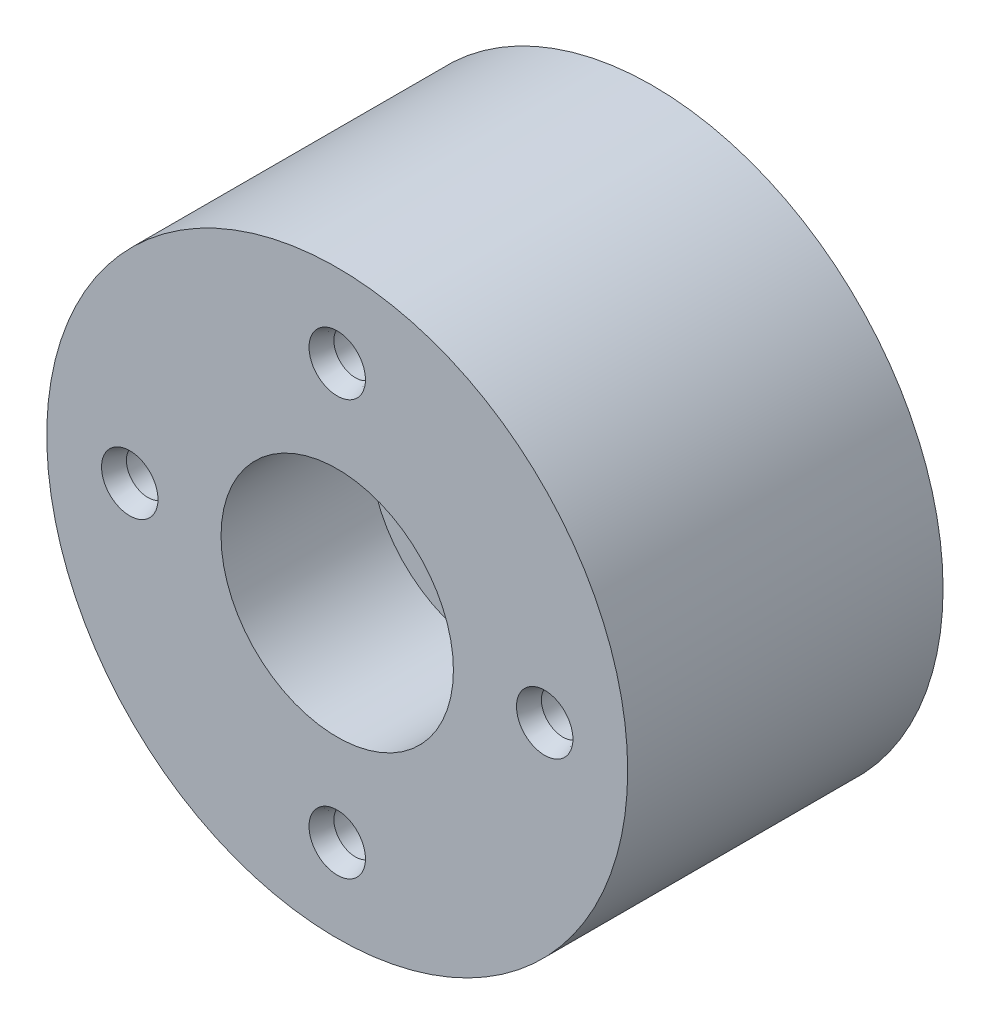
SolidWorks part; units mm, degrees
ref_plane "前视基准面" through (0, 0, 0) normal (0, 0, 1) x (1, 0, 0)
ref_plane "上视基准面" through (0, 0, 0) normal (0, 1, 0) x (1, 0, 0)
ref_plane "右视基准面" through (0, 0, 0) normal (1, 0, 0) x (0, 0, -1)
other "Configuration Table"
sketch "草图1" plane through (0, 0, 0) normal (0, 0, 1) x (1, 0, 0)
  circle A0 centre (0, 0) radius 17.5
extrude "凸台-拉伸1" add sketch "草图1" against normal blind 19
sketch "草图2" plane through (0, 0, 0) normal (0, 0, 1) x (1, 0, 0)
  circle A0 centre (12.5, 0) radius 1.3
  circle A1 centre (0, -12.5) radius 1.3
  circle A2 centre (-12.5, 0) radius 1.3
  circle A3 centre (0, 12.5) radius 1.3
  point P11 (0, 0)
  dimension "D1" = 4
extrude "切除-拉伸1" cut sketch "草图2" against normal blind 8
sketch "草图4" plane through (0, 0, 0) normal (0, 0, 1) x (1, 0, 0)
  circle A0 centre (0, 0) radius 7
extrude "切除-拉伸3" cut sketch "草图4" against normal offset from surface (9 mm away) 10 up to face at (17.5, 0, -19)
sketch "草图5" plane through (0, 0, -9) normal (0, 0, 1) x (1, 0, 0)
  circle A0 centre (0, 0) radius 5.55
extrude "切除-拉伸4" cut sketch "草图5" against normal up to surface (10 mm away) up to face at (17.5, 0, -19)
sketch "草图7" plane through (0, 0, -19) normal (0, 0, -1) x (-1, 0, 0)
  line L0 (4.6927, 14.8832) -> (13.1615, -8.3848) construction
  line L1 (0, 19.1827) -> (0, 0) construction
  line L2 (0, 0) -> (4.6927, 14.8832) construction
  line L3 (0, 0) -> (25.0264, 0) construction
  line L4 (0, 0) -> (13.1615, -8.3848) construction
  line L5 (4.6927, 14.8832) -> (5.256, 13.3355)
  line L6 (5.256, 13.3355) -> (5.8193, 11.7878)
  line L7 (5.8193, 11.7878) -> (6.3826, 10.2402)
  line L8 (6.3826, 10.2402) -> (6.9459, 8.6925)
  line L9 (6.9459, 8.6925) -> (7.5092, 7.1448)
  line L10 (7.5092, 7.1448) -> (8.0725, 5.5971)
  line L11 (8.0725, 5.5971) -> (8.6358, 4.0495)
  line L12 (8.6358, 4.0495) -> (9.1991, 2.5018)
  line L13 (9.1991, 2.5018) -> (9.7624, 0.9541)
  line L14 (9.7624, 0.9541) -> (10.3257, -0.5935)
  line L15 (10.3257, -0.5935) -> (10.889, -2.1412)
  line L16 (10.889, -2.1412) -> (11.4523, -3.6889)
  line L17 (11.4523, -3.6889) -> (12.0156, -5.2366)
  line L18 (12.0156, -5.2366) -> (12.5982, -6.8371)
  line L19 (12.5982, -6.8371) -> (13.1615, -8.3848)
  line L20 (0, 0) -> (5.256, 13.3355) construction
  line L21 (0, 0) -> (5.8193, 11.7878) construction
  line L22 (0, 0) -> (6.3826, 10.2402) construction
  line L23 (0, 0) -> (6.9459, 8.6925) construction
  line L24 (0, 0) -> (7.5092, 7.1448) construction
  line L25 (0, 0) -> (8.0725, 5.5971) construction
  line L26 (0, 0) -> (8.6358, 4.0495) construction
  line L27 (0, 0) -> (9.1991, 2.5018) construction
  line L28 (0, 0) -> (9.7624, 0.9541) construction
  line L29 (0, 0) -> (10.3257, -0.5935) construction
  line L30 (0, 0) -> (10.889, -2.1412) construction
  line L31 (0, 0) -> (11.4523, -3.6889) construction
  line L32 (0, 0) -> (12.0156, -5.2366) construction
  line L33 (0, 0) -> (12.5982, -6.8371) construction
  dimension "D1" = 20
  dimension "D2" = 9.5
  dimension "D3" = 72.5
  dimension "D4" = 32.5
sketch "草图8" plane through (0, 0, -19) normal (0, 0, -1) x (-1, 0, 0)
  line L0 (0, 0) -> (14.7594, -9.4027) construction
  line L1 (0, 0) -> (24.0144, 0) construction
  line L2 (0, 0) -> (16.5957, 5.5528) construction
  line L3 (0, 0) -> (3.4889, 17.1487) construction
  line L4 (0, 0) -> (6.2949, 7.1151) construction
  line L5 (0, 0) -> (15.1732, 5.0769)
  circle A0 centre (0, 0) radius 17.5 construction
  point P12 (0, 0)
  point P26 (0, 0)
  point P27 (0, 0)
  dimension "D1" = 32.5
  dimension "D2" = 51
  dimension "D4" = 9.5
  dimension "D5" = 30
  dimension "D7" = 16
sketch "草图11" plane through (0, 0, -19) normal (0, 0, -1) x (-1, 0, 0)
  line L0 (15.1732, 5.0769) -> (8.0557, 4.0132) construction
  line L1 (0, 0) -> (8.0557, 4.0132) construction
  line L3 (15.9006, 7.3089) -> (7.7453, 6.0901)
  line L4 (17.1945, 3.2556) -> (8.3661, 1.9362)
  line L5 (14.8628, 7.1538) -> (7.7453, 6.0901) construction
  line L18 (15.4836, 2.9999) -> (8.3661, 1.9362) construction
  line L19 (0, 0) -> (15.1732, 5.0769) construction
  arc A0 (7.7453, 6.0901) -> (8.3661, 1.9362) centre (8.0557, 4.0132) ccw
  circle A4 centre (0, 0) radius 17.5
  arc A6 (17.1945, 3.2556) -> (15.9006, 7.3089) centre (0, 0) ccw
  point P15 (0, 0)
  dimension "D4" = 10
  dimension "D1" = 9
  dimension "D3" = 2.1
  dimension "D5" = 0
extrude "切除-拉伸6" cut sketch "草图11" against normal blind 8
fillet "圆角1" radius 1 3 edges at (-12.7803, 2.5959, -11) (-5.9788, 3.7028, -11) (-11.823, 6.6995, -11)
fillet "圆角2" radius 0.5 5 edges at (-17.1945, 3.2556, -15.5) (-17.1207, 3.6236, -11.2196) (-16.6759, 5.3072, -11) (-15.9886, 7.1144, -11.3929) (-15.9006, 7.3089, -15.5)
chamfer "倒角1" distance 0.9 angle 60 1 edges at (5.55, 0, -19)
chamfer "倒角2" distance 0.4 angle 70 4 edges at (-11.2, 0, 0) (1.3, -12.5, 0) (13.8, 0, 0) (1.3, 12.5, 0)
